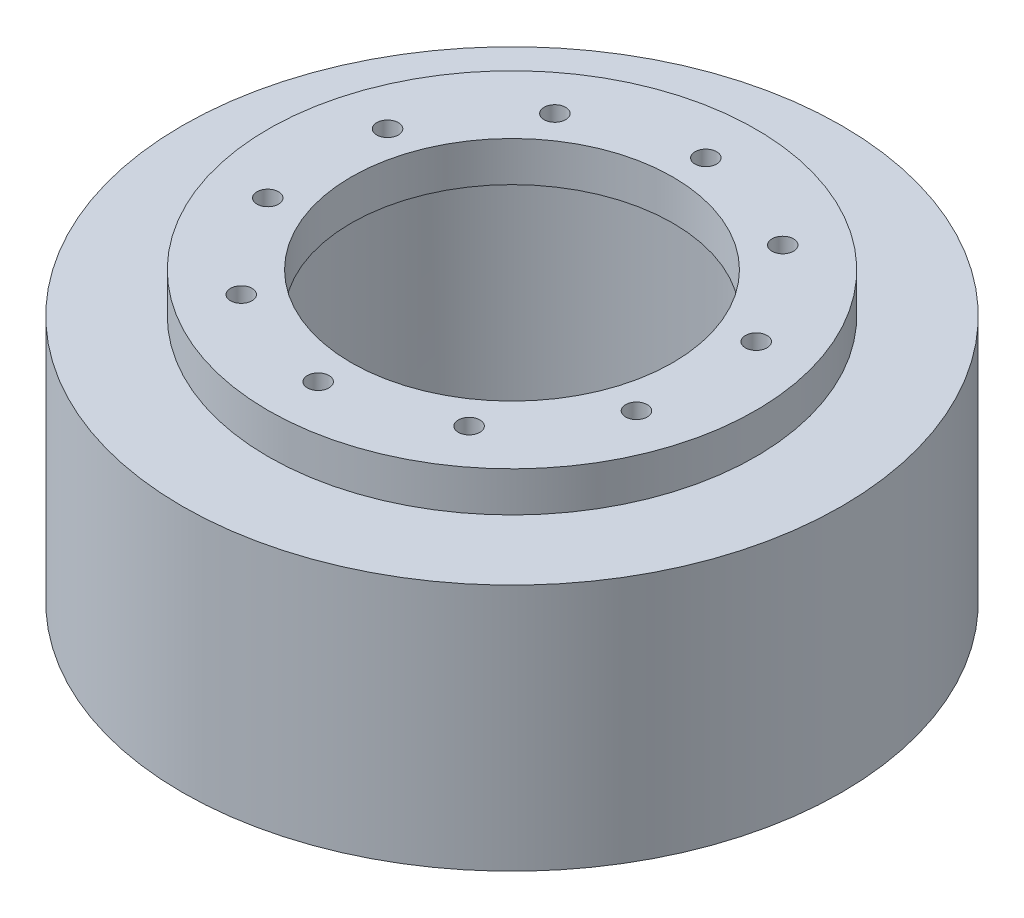
SolidWorks part; units mm, degrees
material "Custom PLA"
ref_plane "Front Plane" through (0, 0, 0) normal (0, 0, 1) x (1, 0, 0)
ref_plane "Top Plane" through (0, 0, 0) normal (0, 1, 0) x (1, 0, 0)
ref_plane "Right Plane" through (0, 0, 0) normal (1, 0, 0) x (0, 0, -1)
sketch "Sketch1" plane through (0, 0, 0) normal (0, 1, 0) x (1, 0, 0)
  circle A0 centre (0, 0) radius 82.5
  circle A1 centre (0, 0) radius 55
  dimension "D1" = 165
  dimension "D2" = 110
extrude "Boss-Extrude1" add sketch "Sketch1" along normal blind 62
sketch "Sketch3" plane through (0, 0, 0) normal (0, -1, 0) x (1, 0, 0)
  line L0 (-15.3096, -31.474) -> (-15.3096, -47.5985)
  line L1 (16.6904, -30.7641) -> (16.6904, -47.1321)
  line L2 (-15.3096, -47.5985) -> (16.6904, -47.1321) construction
  line L3 (-49.7144, 5.3361) -> (49.4388, 5.3361) construction
  line L4 (49.7144, 5.3361) -> (78, 5.3361)
  line L5 (49.5539, -6.6639) -> (78, -6.6639)
  line L6 (78, 5.3361) -> (78, -6.6639)
  line L7 (-49.7144, 5.3361) -> (-78, 5.3361)
  line L8 (-49.5539, -6.6639) -> (-78, -6.6639)
  line L9 (-78, 5.3361) -> (-78, -6.6639)
  arc A0 (16.6904, -47.1321) -> (49.5539, -6.6639) centre (0, 0) ccw
  arc A1 (16.6904, -30.7641) -> (-15.3096, -31.474) centre (0, 0) ccw
  arc A2 (-49.5539, -6.6639) -> (-15.3096, -47.5985) centre (0, 0) ccw
  arc A3 (49.7144, 5.3361) -> (-49.7144, 5.3361) centre (0, 0) ccw
  dimension "D1" = 35
  dimension "D2" = 50
  dimension "D3" = 32
  dimension "D4" = 47.3703
  dimension "D5" = 28.4461
  dimension "D6" = 78
  dimension "D7" = 12
  dimension "D8" = 12
  dimension "D9" = 78
extrude "Cut-Extrude1" [suppressed] cut sketch "Sketch3" against normal blind 12
sketch "Sketch6" plane through (0, 62, 0) normal (0, 1, 0) x (1, 0, 0)
  circle A0 centre (0, 0) radius 61
  dimension "D1" = 122
extrude "Boss-Extrude4" add sketch "Sketch6" along normal blind 10
sketch "Sketch8" plane through (0, 72, 0) normal (0, 1, 0) x (1, 0, 0)
  circle A0 centre (0, 0) radius 40.25
  dimension "D1" = 80.5
extrude "Cut-Extrude4" cut sketch "Sketch8" against normal blind 10
sketch "Sketch9" plane through (0, 72, 0) normal (0, 1, 0) x (1, 0, 0)
  line L0 (0, 48.5) -> (0, 0) construction
  line L1 (0, 61) -> (0, 45.8) construction
  circle A0 centre (0, 48.5) radius 2.7
  circle A1 centre (0, 0) radius 61 construction
  circle A2 centre (0, 0) radius 61 construction
  circle A3 centre (0, 0) radius 48.5 construction
  dimension "D2" = 5.4
  dimension "D1" = 97
extrude "Cut-Extrude5" cut sketch "Sketch9" against normal blind 30 contours A0
pattern_circular "CirPattern6" count 10 over 360 about axis through (0, 0, 0) along (0, 1, 0) of "Cut-Extrude5"
sketch "Sketch10" plane through (0, 0, 0) normal (0, -1, 0) x (1, 0, 0)
  line L0 (0, 107.5596) -> (0, -134.3043) construction
  line L1 (-148.8873, 0) -> (157.7068, 0) construction
  circle A0 centre (0, 0) radius 69.5 construction
  circle A1 centre (0, 0) radius 82.5 construction
  circle A2 centre (0, 69.5) radius 4.66
  dimension "D1" = 13
  dimension "D2" = 9.32
extrude "Cut-Extrude6" cut sketch "Sketch10" against normal blind 7.62
pattern_circular "CirPattern7" count 6 over 360 about axis through (0, 0, 0) along (0, 1, 0) of "Cut-Extrude6"
sketch "Sketch12" plane through (0, 0, 0) normal (0, -1, 0) x (1, 0, 0)
  line L0 (-110.4727, 0) -> (144.8018, 0) construction
  line L1 (71.0368, -20.5) -> (51.0368, -20.5)
  line L2 (71.0368, -20.5) -> (71.0368, 20.5)
  line L3 (71.0368, 20.5) -> (51.0368, 20.5)
  line L4 (51.0368, -20.5) -> (51.0368, 20.5)
  circle A0 centre (0, 0) radius 55 construction
  point P9 (51.0368, 0)
  dimension "D1" = 41
  dimension "D2" = 20
extrude "Cut-Extrude7" cut sketch "Sketch12" against normal blind 11.3
mirror "Mirror1" about plane through (0, 0, 0) normal (1, 0, 0) of "Cut-Extrude7"
sketch "Sketch13" plane through (0, 11.3, 0) normal (0, -1, 0) x (1, 0, 0)
  line L0 (63, 20.5) -> (63, -20.5) construction
  line L6 (71.0368, 20.5) -> (51.0368, 20.5) construction
  line L7 (55, 20.5) -> (55, -20.5) construction
  circle A0 centre (63, 10.5) radius 4.66
  circle A1 centre (0, 0) radius 55 construction
  point P6 (55, 0)
  dimension "D2" = 9.32
  dimension "D3" = 10
  dimension "D1" = 8
extrude "Cut-Extrude8" cut sketch "Sketch13" against normal blind 7.62 contours A0
mirror "Mirror2" about plane through (0, 0, 0) normal (1, 0, 0) of "Cut-Extrude8" second plane through (0, 0, 0) second plane normal (0, 0, 1)
